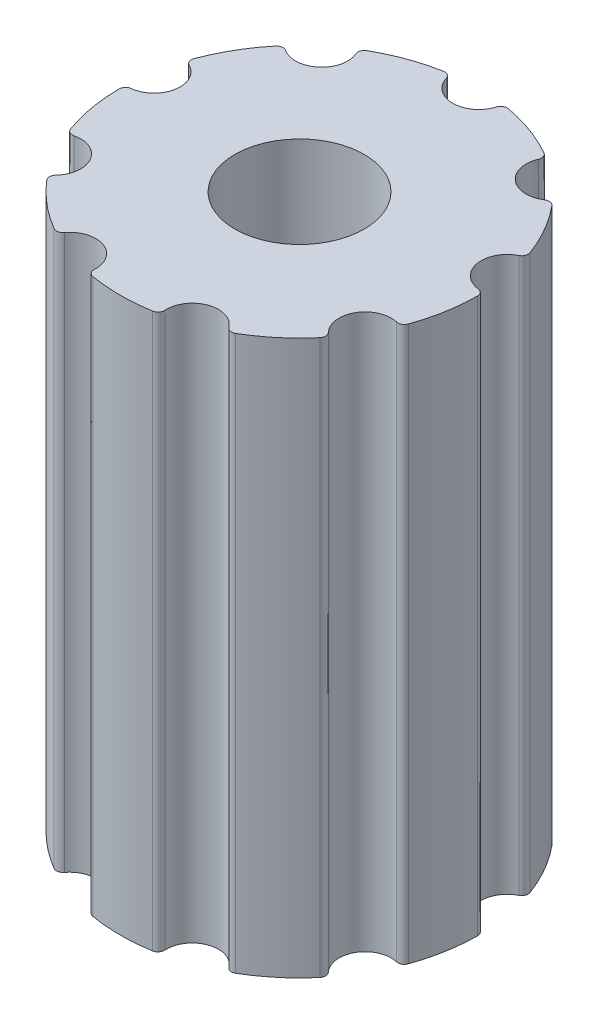
SolidWorks part; units mm, degrees
ref_plane "Front Plane" through (0, 0, 0) normal (0, 0, 1) x (1, 0, 0)
ref_plane "Top Plane" through (0, 0, 0) normal (0, 1, 0) x (1, 0, 0)
ref_plane "Right Plane" through (0, 0, 0) normal (1, 0, 0) x (0, 0, -1)
sketch "Sketch1" plane through (0, 0, 0) normal (0, 1, 0) x (1, 0, 0)
  arc A0 (-0.994, 5.4094) -> (-2.7157, 4.7828) centre (0, 0) ccw
  arc A1 (-0.7663, 5.2702) -> (0.7663, 5.2702) centre (0, 5.5) ccw
  arc A2 (0.7663, 5.2702) -> (0.994, 5.4094) centre (0.9578, 5.2127) cw
  arc A3 (-0.7663, 5.2702) -> (-0.994, 5.4094) centre (-0.9578, 5.2127) ccw
  arc A4 (2.8006, 4.5297) -> (3.9746, 3.5446) centre (3.5353, 4.2132) ccw
  arc A5 (3.9746, 3.5446) -> (4.2386, 3.5049) centre (4.0844, 3.3775) cw
  arc A6 (2.8006, 4.5297) -> (2.7157, 4.7828) centre (2.6169, 4.6089) ccw
  arc A7 (5.0571, 1.6698) -> (5.3232, 0.1605) centre (5.4164, 0.9551) ccw
  arc A8 (5.3232, 0.1605) -> (5.4999, -0.0396) centre (5.2999, -0.0381) cw
  arc A9 (5.0571, 1.6698) -> (5.1546, 1.9182) centre (4.9672, 1.8485) ccw
  arc A10 (4.9473, -1.9715) -> (4.181, -3.2987) centre (4.7631, -2.75) ccw
  arc A11 (4.181, -3.2987) -> (4.1877, -3.5655) centre (4.0354, -3.4359) cw
  arc A12 (4.9473, -1.9715) -> (5.1817, -1.8439) centre (4.9933, -1.7768) ccw
  arc A13 (2.5226, -4.6903) -> (1.0824, -5.2144) centre (1.8811, -5.1683) ccw
  arc A14 (1.0824, -5.2144) -> (0.9161, -5.4232) centre (0.8828, -5.226) cw
  arc A15 (2.5226, -4.6903) -> (2.7842, -4.7432) centre (2.6829, -4.5708) ccw
  arc A16 (-1.0824, -5.2144) -> (-2.5226, -4.6903) centre (-1.8811, -5.1683) ccw
  arc A17 (-2.5226, -4.6903) -> (-2.7842, -4.7432) centre (-2.6829, -4.5708) cw
  arc A18 (-1.0824, -5.2144) -> (-0.9161, -5.4232) centre (-0.8828, -5.226) ccw
  arc A19 (-4.181, -3.2987) -> (-4.9473, -1.9715) centre (-4.7631, -2.75) ccw
  arc A20 (-4.9473, -1.9715) -> (-5.1817, -1.8439) centre (-4.9933, -1.7768) cw
  arc A21 (-4.181, -3.2987) -> (-4.1877, -3.5655) centre (-4.0354, -3.4359) ccw
  arc A22 (-5.3232, 0.1605) -> (-5.0571, 1.6698) centre (-5.4164, 0.9551) ccw
  arc A23 (-5.0571, 1.6698) -> (-5.1546, 1.9182) centre (-4.9672, 1.8485) cw
  arc A24 (-5.3232, 0.1605) -> (-5.4999, -0.0396) centre (-5.2999, -0.0381) ccw
  arc A25 (-3.9746, 3.5446) -> (-2.8006, 4.5297) centre (-3.5353, 4.2132) ccw
  arc A26 (-2.8006, 4.5297) -> (-2.7157, 4.7828) centre (-2.6169, 4.6089) cw
  arc A27 (-3.9746, 3.5446) -> (-4.2386, 3.5049) centre (-4.0844, 3.3775) ccw
  arc A28 (-4.2386, 3.5049) -> (-5.1546, 1.9182) centre (0, 0) ccw
  arc A29 (-5.4999, -0.0396) -> (-5.1817, -1.8439) centre (0, 0) ccw
  arc A30 (-4.1877, -3.5655) -> (-2.7842, -4.7432) centre (0, 0) ccw
  arc A31 (-0.9161, -5.4232) -> (0.9161, -5.4232) centre (0, 0) ccw
  arc A32 (2.7842, -4.7432) -> (4.1877, -3.5655) centre (0, 0) ccw
  arc A33 (5.1817, -1.8439) -> (5.4999, -0.0396) centre (0, 0) ccw
  arc A34 (5.1546, 1.9182) -> (4.2386, 3.5049) centre (0, 0) ccw
  arc A35 (2.7157, 4.7828) -> (0.994, 5.4094) centre (0, 0) ccw
  circle A36 centre (0, 0) radius 1.985
  point P67 (0, 0)
  dimension "D1" = 11
  dimension "D2" = 1.6
  dimension "D3" = 0.2
  dimension "D5" = 3.97
  dimension "D4" = 9
extrude "Boss-Extrude1" add sketch "Sketch1" along normal blind 17
sketch "Sketch2" plane through (0, 0, 0) normal (0, 0, 1) x (1, 0, 0)
  line L0 (0, 0) -> (0, 27.4519) construction
  line L1 (-5.4999, 17) -> (-6, 18.0002)
  line L3 (-6, 25.0002) -> (-1.95, 25.0002)
  line L5 (-1.95, 17) -> (-5.4999, 17)
  line L6 (-6, 18.0002) -> (-6, 25.0002)
  line L7 (-1.95, 25.0002) -> (-1.95, 17)
  dimension "D1" = 7
  dimension "D2" = 3.9
  dimension "D3" = 12
revolve "Revolve1" [suppressed] add sketch "Sketch2" angle 360 about L0
